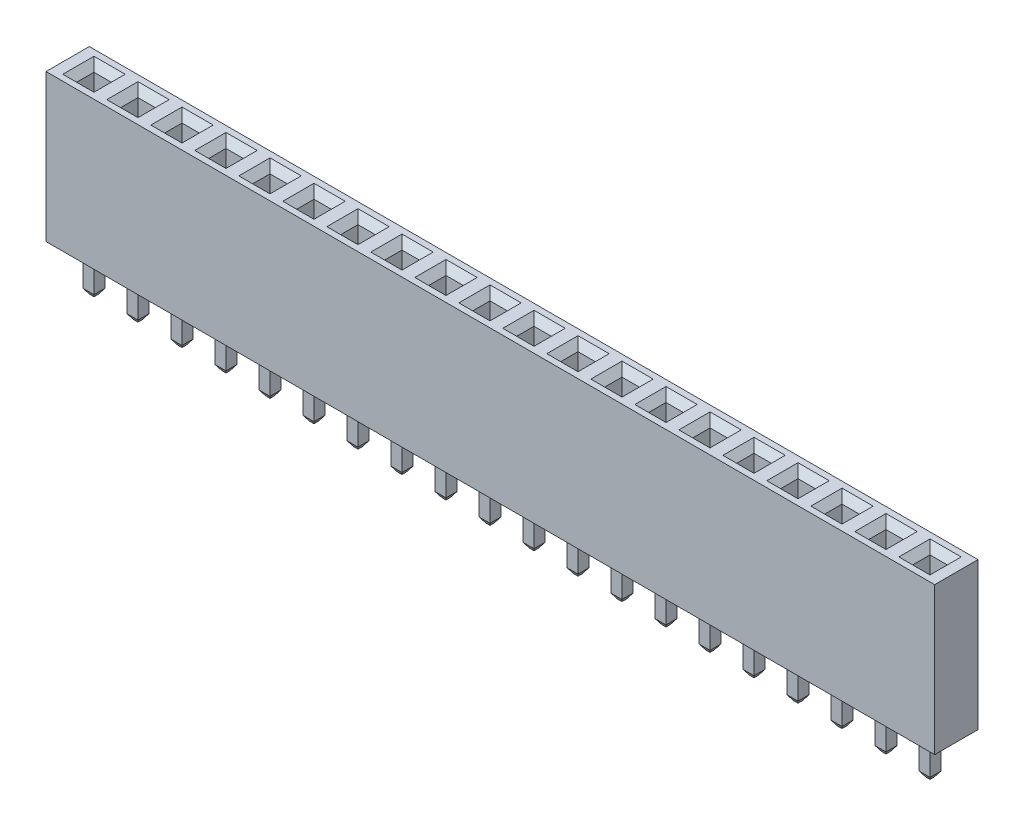
SolidWorks part; units mm, degrees
ref_plane "Front" through (0, 0, 0) normal (0, 0, 1) x (1, 0, 0)
ref_plane "Top" through (0, 0, 0) normal (0, 1, 0) x (1, 0, 0)
ref_plane "Right" through (0, 0, 0) normal (1, 0, 0) x (0, 0, -1)
sketch "Sketch1" plane through (0, 0, 0) normal (0, 1, 0) x (1, 0, 0)
  line L1 (0, 0) -> (51.3, 0)
  line L2 (0, 0) -> (0, 2.5)
  line L3 (0, 2.5) -> (51.3, 2.5)
  line L4 (51.3, 0) -> (51.3, 2.5)
  dimension "D1" = 51.3
  dimension "D2" = 2.5
extrude "Boss-Extrude1" add sketch "Sketch1" along normal blind 8.5
sketch "Sketch2" plane through (0, 0, 0) normal (0, -1, 0) x (1, 0, 0)
  line L0 (0, 0) -> (51.3, 0) construction
  line L1 (1.2, -0.93) -> (1.84, -0.93)
  line L2 (1.2, -0.93) -> (1.2, -1.57)
  line L3 (1.2, -1.57) -> (1.84, -1.57)
  line L4 (1.84, -0.93) -> (1.84, -1.57)
  line L5 (0, -2.5) -> (0, 0) construction
  line L6 (3.74, -0.93) -> (4.38, -0.93)
  line L7 (3.74, -0.93) -> (3.74, -1.57)
  line L8 (3.74, -1.57) -> (4.38, -1.57)
  line L9 (4.38, -0.93) -> (4.38, -1.57)
  line L10 (6.28, -0.93) -> (6.92, -0.93)
  line L11 (6.28, -0.93) -> (6.28, -1.57)
  line L12 (6.28, -1.57) -> (6.92, -1.57)
  line L13 (6.92, -0.93) -> (6.92, -1.57)
  line L14 (8.82, -0.93) -> (9.46, -0.93)
  line L15 (8.82, -0.93) -> (8.82, -1.57)
  line L16 (8.82, -1.57) -> (9.46, -1.57)
  line L17 (9.46, -0.93) -> (9.46, -1.57)
  line L18 (11.36, -0.93) -> (12, -0.93)
  line L19 (11.36, -0.93) -> (11.36, -1.57)
  line L20 (11.36, -1.57) -> (12, -1.57)
  line L21 (12, -0.93) -> (12, -1.57)
  line L22 (13.9, -0.93) -> (14.54, -0.93)
  line L23 (13.9, -0.93) -> (13.9, -1.57)
  line L24 (13.9, -1.57) -> (14.54, -1.57)
  line L25 (14.54, -0.93) -> (14.54, -1.57)
  line L26 (16.44, -0.93) -> (17.08, -0.93)
  line L27 (16.44, -0.93) -> (16.44, -1.57)
  line L28 (16.44, -1.57) -> (17.08, -1.57)
  line L29 (17.08, -0.93) -> (17.08, -1.57)
  line L30 (18.98, -0.93) -> (19.62, -0.93)
  line L31 (18.98, -0.93) -> (18.98, -1.57)
  line L32 (18.98, -1.57) -> (19.62, -1.57)
  line L33 (19.62, -0.93) -> (19.62, -1.57)
  line L34 (21.52, -0.93) -> (22.16, -0.93)
  line L35 (21.52, -0.93) -> (21.52, -1.57)
  line L36 (21.52, -1.57) -> (22.16, -1.57)
  line L37 (22.16, -0.93) -> (22.16, -1.57)
  line L38 (24.06, -0.93) -> (24.7, -0.93)
  line L39 (24.06, -0.93) -> (24.06, -1.57)
  line L40 (24.06, -1.57) -> (24.7, -1.57)
  line L41 (24.7, -0.93) -> (24.7, -1.57)
  line L42 (26.6, -0.93) -> (27.24, -0.93)
  line L43 (26.6, -0.93) -> (26.6, -1.57)
  line L44 (26.6, -1.57) -> (27.24, -1.57)
  line L45 (27.24, -0.93) -> (27.24, -1.57)
  line L46 (29.14, -0.93) -> (29.78, -0.93)
  line L47 (29.14, -0.93) -> (29.14, -1.57)
  line L48 (29.14, -1.57) -> (29.78, -1.57)
  line L49 (29.78, -0.93) -> (29.78, -1.57)
  line L50 (31.68, -0.93) -> (32.32, -0.93)
  line L51 (31.68, -0.93) -> (31.68, -1.57)
  line L52 (31.68, -1.57) -> (32.32, -1.57)
  line L53 (32.32, -0.93) -> (32.32, -1.57)
  line L54 (34.22, -0.93) -> (34.86, -0.93)
  line L55 (34.22, -0.93) -> (34.22, -1.57)
  line L56 (34.22, -1.57) -> (34.86, -1.57)
  line L57 (34.86, -0.93) -> (34.86, -1.57)
  line L58 (36.76, -0.93) -> (37.4, -0.93)
  line L59 (36.76, -0.93) -> (36.76, -1.57)
  line L60 (36.76, -1.57) -> (37.4, -1.57)
  line L61 (37.4, -0.93) -> (37.4, -1.57)
  line L62 (39.3, -0.93) -> (39.94, -0.93)
  line L63 (39.3, -0.93) -> (39.3, -1.57)
  line L64 (39.3, -1.57) -> (39.94, -1.57)
  line L65 (39.94, -0.93) -> (39.94, -1.57)
  line L66 (41.84, -0.93) -> (42.48, -0.93)
  line L67 (41.84, -0.93) -> (41.84, -1.57)
  line L68 (41.84, -1.57) -> (42.48, -1.57)
  line L69 (42.48, -0.93) -> (42.48, -1.57)
  line L70 (44.38, -0.93) -> (45.02, -0.93)
  line L71 (44.38, -0.93) -> (44.38, -1.57)
  line L72 (44.38, -1.57) -> (45.02, -1.57)
  line L73 (45.02, -0.93) -> (45.02, -1.57)
  line L74 (46.92, -0.93) -> (47.56, -0.93)
  line L75 (46.92, -0.93) -> (46.92, -1.57)
  line L76 (46.92, -1.57) -> (47.56, -1.57)
  line L77 (47.56, -0.93) -> (47.56, -1.57)
  line L78 (49.46, -0.93) -> (50.1, -0.93)
  line L79 (49.46, -0.93) -> (49.46, -1.57)
  line L80 (49.46, -1.57) -> (50.1, -1.57)
  line L81 (50.1, -0.93) -> (50.1, -1.57)
  dimension "D1" = 0.64
  dimension "D2" = 0.64
  dimension "D3" = 0.93
  dimension "D4" = 1.2
  dimension "D5" = 20
extrude "Boss-Extrude2" add sketch "Sketch2" along normal blind 2.5
chamfer "Chamfer1" distance 0.3 angle 33 80 edges at (49.78, -2.5, -0.93) (50.1, -2.5, -1.25) (49.78, -2.5, -1.57) (49.46, -2.5, -1.25) (47.24, -2.5, -0.93) (47.56, -2.5, -1.25) (47.24, -2.5, -1.57) (46.92, -2.5, -1.25) (44.7, -2.5, -0.93) (45.02, -2.5, -1.25) (44.7, -2.5, -1.57) (44.38, -2.5, -1.25) (42.16, -2.5, -0.93) (42.48, -2.5, -1.25) (42.16, -2.5, -1.57) (41.84, -2.5, -1.25) (39.62, -2.5, -0.93) (39.94, -2.5, -1.25) (39.62, -2.5, -1.57) (39.3, -2.5, -1.25) (37.08, -2.5, -0.93) (37.4, -2.5, -1.25) (37.08, -2.5, -1.57) (36.76, -2.5, -1.25) (34.54, -2.5, -0.93) (34.86, -2.5, -1.25) (34.54, -2.5, -1.57) (34.22, -2.5, -1.25) (32, -2.5, -0.93) (32.32, -2.5, -1.25) (32, -2.5, -1.57) (31.68, -2.5, -1.25) (29.46, -2.5, -0.93) (29.78, -2.5, -1.25) (29.46, -2.5, -1.57) (29.14, -2.5, -1.25) (26.92, -2.5, -0.93) (27.24, -2.5, -1.25) (26.92, -2.5, -1.57) (26.6, -2.5, -1.25) (24.38, -2.5, -0.93) (24.7, -2.5, -1.25) (24.38, -2.5, -1.57) (24.06, -2.5, -1.25) (21.84, -2.5, -0.93) (22.16, -2.5, -1.25) (21.84, -2.5, -1.57) (21.52, -2.5, -1.25) (19.3, -2.5, -0.93) (19.62, -2.5, -1.25) (19.3, -2.5, -1.57) (18.98, -2.5, -1.25) (16.76, -2.5, -0.93) (17.08, -2.5, -1.25) (16.76, -2.5, -1.57) (16.44, -2.5, -1.25) (14.22, -2.5, -0.93) (14.54, -2.5, -1.25) (14.22, -2.5, -1.57) (13.9, -2.5, -1.25) (11.68, -2.5, -0.93) (12, -2.5, -1.25) (11.68, -2.5, -1.57) (11.36, -2.5, -1.25) (9.14, -2.5, -0.93) (9.46, -2.5, -1.25) (9.14, -2.5, -1.57) (8.82, -2.5, -1.25) (6.6, -2.5, -0.93) (6.92, -2.5, -1.25) (6.6, -2.5, -1.57) (6.28, -2.5, -1.25) (4.06, -2.5, -0.93) (4.38, -2.5, -1.25) (4.06, -2.5, -1.57) (3.74, -2.5, -1.25) (1.52, -2.5, -0.93) (1.84, -2.5, -1.25) (1.52, -2.5, -1.57) (1.2, -2.5, -1.25)
sketch "Sketch3" plane through (0, 8.5, 0) normal (0, 1, 0) x (1, 0, 0)
  line L0 (51.3, 0) -> (51.3, 2.5) construction
  line L1 (50.28, 0.75) -> (49.28, 0.75)
  line L2 (50.28, 0.75) -> (50.28, 1.75)
  line L3 (50.28, 1.75) -> (49.28, 1.75)
  line L4 (49.28, 0.75) -> (49.28, 1.75)
  line L5 (0, 0) -> (51.3, 0) construction
  line L7 (47.74, 0.75) -> (46.74, 0.75)
  line L8 (47.74, 0.75) -> (47.74, 1.75)
  line L9 (47.74, 1.75) -> (46.74, 1.75)
  line L10 (46.74, 0.75) -> (46.74, 1.75)
  line L11 (45.2, 0.75) -> (44.2, 0.75)
  line L12 (45.2, 0.75) -> (45.2, 1.75)
  line L13 (45.2, 1.75) -> (44.2, 1.75)
  line L14 (44.2, 0.75) -> (44.2, 1.75)
  line L15 (42.66, 0.75) -> (41.66, 0.75)
  line L16 (42.66, 0.75) -> (42.66, 1.75)
  line L17 (42.66, 1.75) -> (41.66, 1.75)
  line L18 (41.66, 0.75) -> (41.66, 1.75)
  line L19 (40.12, 0.75) -> (39.12, 0.75)
  line L20 (40.12, 0.75) -> (40.12, 1.75)
  line L21 (40.12, 1.75) -> (39.12, 1.75)
  line L22 (39.12, 0.75) -> (39.12, 1.75)
  line L23 (37.58, 0.75) -> (36.58, 0.75)
  line L24 (37.58, 0.75) -> (37.58, 1.75)
  line L25 (37.58, 1.75) -> (36.58, 1.75)
  line L26 (36.58, 0.75) -> (36.58, 1.75)
  line L27 (35.04, 0.75) -> (34.04, 0.75)
  line L28 (35.04, 0.75) -> (35.04, 1.75)
  line L29 (35.04, 1.75) -> (34.04, 1.75)
  line L30 (34.04, 0.75) -> (34.04, 1.75)
  line L31 (32.5, 0.75) -> (31.5, 0.75)
  line L32 (32.5, 0.75) -> (32.5, 1.75)
  line L33 (32.5, 1.75) -> (31.5, 1.75)
  line L34 (31.5, 0.75) -> (31.5, 1.75)
  line L35 (29.96, 0.75) -> (28.96, 0.75)
  line L36 (29.96, 0.75) -> (29.96, 1.75)
  line L37 (29.96, 1.75) -> (28.96, 1.75)
  line L38 (28.96, 0.75) -> (28.96, 1.75)
  line L39 (27.42, 0.75) -> (26.42, 0.75)
  line L40 (27.42, 0.75) -> (27.42, 1.75)
  line L41 (27.42, 1.75) -> (26.42, 1.75)
  line L42 (26.42, 0.75) -> (26.42, 1.75)
  line L43 (24.88, 0.75) -> (23.88, 0.75)
  line L44 (24.88, 0.75) -> (24.88, 1.75)
  line L45 (24.88, 1.75) -> (23.88, 1.75)
  line L46 (23.88, 0.75) -> (23.88, 1.75)
  line L47 (22.34, 0.75) -> (21.34, 0.75)
  line L48 (22.34, 0.75) -> (22.34, 1.75)
  line L49 (22.34, 1.75) -> (21.34, 1.75)
  line L50 (21.34, 0.75) -> (21.34, 1.75)
  line L51 (19.8, 0.75) -> (18.8, 0.75)
  line L52 (19.8, 0.75) -> (19.8, 1.75)
  line L53 (19.8, 1.75) -> (18.8, 1.75)
  line L54 (18.8, 0.75) -> (18.8, 1.75)
  line L55 (17.26, 0.75) -> (16.26, 0.75)
  line L56 (17.26, 0.75) -> (17.26, 1.75)
  line L57 (17.26, 1.75) -> (16.26, 1.75)
  line L58 (16.26, 0.75) -> (16.26, 1.75)
  line L59 (14.72, 0.75) -> (13.72, 0.75)
  line L60 (14.72, 0.75) -> (14.72, 1.75)
  line L61 (14.72, 1.75) -> (13.72, 1.75)
  line L62 (13.72, 0.75) -> (13.72, 1.75)
  line L63 (12.18, 0.75) -> (11.18, 0.75)
  line L64 (12.18, 0.75) -> (12.18, 1.75)
  line L65 (12.18, 1.75) -> (11.18, 1.75)
  line L66 (11.18, 0.75) -> (11.18, 1.75)
  line L67 (9.64, 0.75) -> (8.64, 0.75)
  line L68 (9.64, 0.75) -> (9.64, 1.75)
  line L69 (9.64, 1.75) -> (8.64, 1.75)
  line L70 (8.64, 0.75) -> (8.64, 1.75)
  line L71 (7.1, 0.75) -> (6.1, 0.75)
  line L72 (7.1, 0.75) -> (7.1, 1.75)
  line L73 (7.1, 1.75) -> (6.1, 1.75)
  line L74 (6.1, 0.75) -> (6.1, 1.75)
  line L75 (4.56, 0.75) -> (3.56, 0.75)
  line L76 (4.56, 0.75) -> (4.56, 1.75)
  line L77 (4.56, 1.75) -> (3.56, 1.75)
  line L78 (3.56, 0.75) -> (3.56, 1.75)
  line L79 (2.02, 0.75) -> (1.02, 0.75)
  line L80 (2.02, 0.75) -> (2.02, 1.75)
  line L81 (2.02, 1.75) -> (1.02, 1.75)
  line L82 (1.02, 0.75) -> (1.02, 1.75)
  dimension "D1" = 1
  dimension "D2" = 1
  dimension "D3" = 1.02
  dimension "D4" = 0.75
  dimension "D5" = 20
extrude "Cut-Extrude1" cut sketch "Sketch3" against normal blind 6
chamfer "Chamfer2" distance 0.4 angle 45 80 edges at (1.02, 8.5, -1.25) (1.52, 8.5, -1.75) (2.02, 8.5, -1.25) (1.52, 8.5, -0.75) (3.56, 8.5, -1.25) (4.06, 8.5, -1.75) (4.56, 8.5, -1.25) (4.06, 8.5, -0.75) (6.1, 8.5, -1.25) (6.6, 8.5, -1.75) (7.1, 8.5, -1.25) (6.6, 8.5, -0.75) (8.64, 8.5, -1.25) (9.14, 8.5, -1.75) (9.64, 8.5, -1.25) (9.14, 8.5, -0.75) (11.68, 8.5, -1.75) (11.18, 8.5, -1.25) (11.68, 8.5, -0.75) (12.18, 8.5, -1.25) (13.72, 8.5, -1.25) (14.22, 8.5, -1.75) (14.72, 8.5, -1.25) (14.22, 8.5, -0.75) (16.26, 8.5, -1.25) (16.76, 8.5, -1.75) (17.26, 8.5, -1.25) (16.76, 8.5, -0.75) (18.8, 8.5, -1.25) (19.3, 8.5, -1.75) (19.8, 8.5, -1.25) (19.3, 8.5, -0.75) (21.34, 8.5, -1.25) (21.84, 8.5, -1.75) (22.34, 8.5, -1.25) (21.84, 8.5, -0.75) (23.88, 8.5, -1.25) (24.38, 8.5, -1.75) (24.88, 8.5, -1.25) (24.38, 8.5, -0.75) (26.42, 8.5, -1.25) (26.92, 8.5, -1.75) (27.42, 8.5, -1.25) (26.92, 8.5, -0.75) (28.96, 8.5, -1.25) (29.46, 8.5, -1.75) (29.96, 8.5, -1.25) (29.46, 8.5, -0.75) (32, 8.5, -1.75) (31.5, 8.5, -1.25) (32, 8.5, -0.75) (32.5, 8.5, -1.25) (34.54, 8.5, -1.75) (34.04, 8.5, -1.25) (35.04, 8.5, -1.25) (34.54, 8.5, -0.75) (36.58, 8.5, -1.25) (37.08, 8.5, -1.75) (37.58, 8.5, -1.25) (37.08, 8.5, -0.75) (39.12, 8.5, -1.25) (39.62, 8.5, -1.75) (39.62, 8.5, -0.75) (40.12, 8.5, -1.25) (42.16, 8.5, -1.75) (41.66, 8.5, -1.25) (42.16, 8.5, -0.75) (42.66, 8.5, -1.25) (44.2, 8.5, -1.25) (44.7, 8.5, -1.75) (45.2, 8.5, -1.25) (44.7, 8.5, -0.75) (46.74, 8.5, -1.25) (47.24, 8.5, -1.75) (47.74, 8.5, -1.25) (47.24, 8.5, -0.75) (50.28, 8.5, -1.25) (49.78, 8.5, -1.75) (49.28, 8.5, -1.25) (49.78, 8.5, -0.75)
